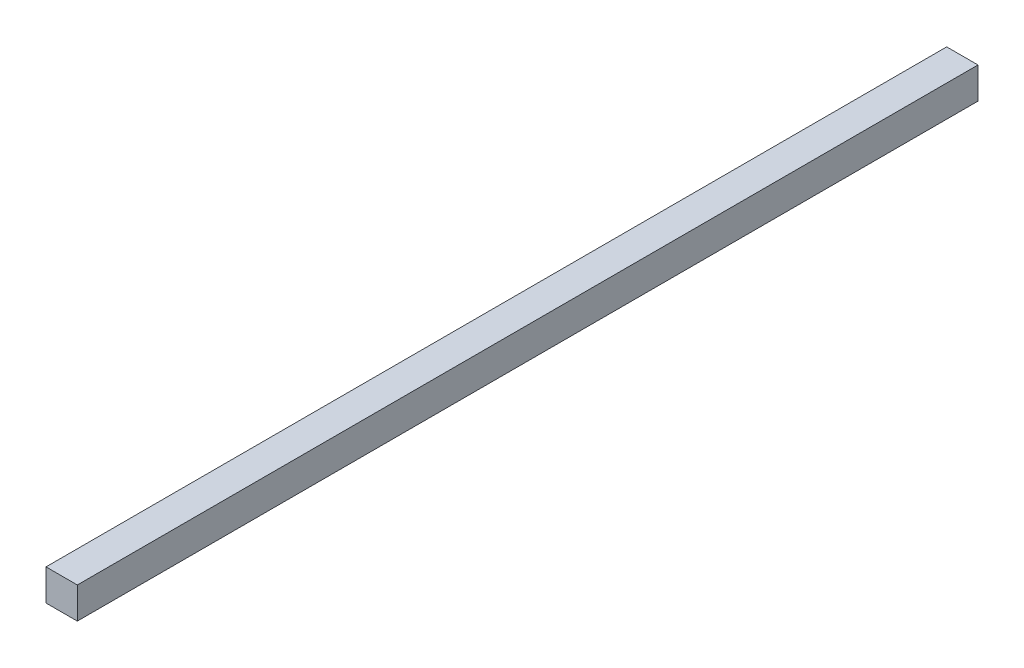
SolidWorks part; units mm, degrees
ref_plane "Front Plane" through (0, 0, 0) normal (0, 0, 1) x (1, 0, 0)
ref_plane "Top Plane" through (0, 0, 0) normal (0, 1, 0) x (1, 0, 0)
ref_plane "Right Plane" through (0, 0, 0) normal (1, 0, 0) x (0, 0, -1)
sketch "Sketch1" plane through (0, 0, 0) normal (0, 0, 1) x (1, 0, 0)
  line L1 (-10, -10) -> (10, -10)
  line L2 (-10, -10) -> (-10, 10)
  line L3 (-10, 10) -> (10, 10)
  line L4 (10, -10) -> (10, 10)
  line L5 (-10, -10) -> (10, 10) construction
  line L6 (-10, 10) -> (10, -10) construction
  point P0 (0, 0)
  dimension "D1" = 20
extrude "Boss-Extrude1" add sketch "Sketch1" along normal blind 575
ref_plane "Plane1" through (0, 0, 0) normal (1, 0, 0) x (0, 0, -1)
